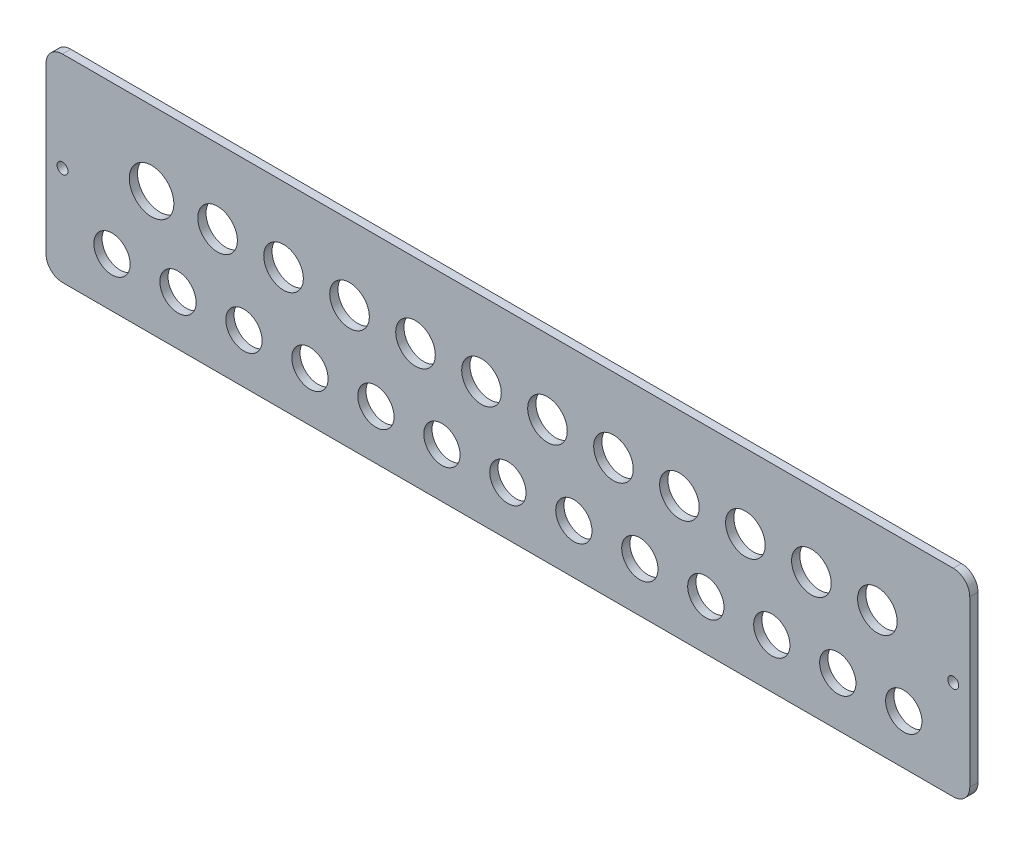
SolidWorks part; units mm, degrees
ref_plane "Front Plane" through (0, 0, 0) normal (0, 0, 1) x (1, 0, 0)
ref_plane "Top Plane" through (0, 0, 0) normal (0, 1, 0) x (1, 0, 0)
ref_plane "Right Plane" through (0, 0, 0) normal (1, 0, 0) x (0, 0, -1)
sketch "Sketch1" plane through (0, 0, 0) normal (0, 0, 1) x (1, 0, 0)
  line L1 (-270, -60) -> (270, -60)
  line L2 (-280, -50) -> (-280, 50)
  line L3 (-270, 60) -> (270, 60)
  line L4 (280, -50) -> (280, 50)
  line L5 (-280, -60) -> (280, 60) construction
  line L6 (-280, 60) -> (280, -60) construction
  arc A0 (280, 50) -> (270, 60) centre (270, 50) ccw
  arc A1 (270, -60) -> (280, -50) centre (270, -50) ccw
  arc A2 (-270, -60) -> (-280, -50) centre (-270, -50) cw
  arc A3 (-280, 50) -> (-270, 60) centre (-270, 50) cw
  point P0 (0, 0)
  dimension "D3" = 10
  dimension "D1" = 560
  dimension "D2" = 120
extrude "Boss-Extrude1" add sketch "Sketch1" along normal blind 5
hole_wizard "M6 Clearance Hole1" positions "Sketch3" profile "Sketch2" hole size "M6" standard "ANSI Metric"
sketch "Sketch3" plane through (0, 0, 5) normal (0, 0, 1) x (1, 0, 0)
  point P0 (270, 0)
  point P3 (-270, 0)
sketch "Sketch2" plane through (270, 0, 5) normal (1, 0, 0) x (0, -1, 0)
  line L0 (0, 0) -> (0, 7.9828)
  line L1 (0, 7.9828) -> (3.3, 6)
  line L2 (3.3, 6) -> (3.3, 0)
  line L5 (3.3, 0) -> (0, 0)
  line L10 (0, 7.9828) -> (-3.3, 6) construction
  line L11 (0, -6.35) -> (0, 107.95) construction
  dimension "Hole Dia." = 6.6
  dimension "Hole Depth" = 6
  dimension "Drill Angle" = 118
hole_wizard "M20 Clearance Hole1" positions "Sketch5" profile "Sketch4" hole size "M20" standard "ANSI Metric"
sketch "Sketch5" plane through (0, 0, 0) normal (0, 0, -1) x (-1, 0, 0)
  line L0 (-280, -50) -> (-280, 50) construction
  line L2 (270, -60) -> (-270, -60) construction
  point P0 (-240, -30)
  point P9 (-229.0327, -60)
  point P16 (-437.7698, 40.5082)
  dimension "D1" = 40
  dimension "D2" = 30
sketch "Sketch4" plane through (240, -30, 0) normal (1, 0, 0) x (0, 1, 0)
  line L0 (0, 0) -> (0, 12.6095)
  line L1 (0, 12.6095) -> (11, 6)
  line L2 (11, 6) -> (11, 0)
  line L5 (11, 0) -> (0, 0)
  line L10 (0, 12.6095) -> (-11, 6) construction
  line L11 (0, -6.35) -> (0, 107.95) construction
  dimension "Hole Dia." = 22
  dimension "Hole Depth" = 6
  dimension "Drill Angle" = 118
pattern_linear "LPattern1" count 13 spacing 40 along (-1, 0, 0) of "M20 Clearance Hole1"
hole_wizard "M22 Clearance Hole1" positions "Sketch7" profile "Sketch6" hole size "M22" standard "ANSI Metric"
sketch "Sketch7" plane through (0, 0, 0) normal (0, 0, -1) x (-1, 0, 0)
  line L0 (-280, -50) -> (-280, 50) construction
  circle A0 centre (-240, -30) radius 11 construction
  point P0 (-224, 15)
  dimension "D1" = 45
  dimension "D2" = 56
sketch "Sketch6" plane through (224, 15, 0) normal (1, 0, 0) x (0, 1, 0)
  line L0 (0, 0) -> (0, 13.2103)
  line L1 (0, 13.2103) -> (12, 6)
  line L2 (12, 6) -> (12, 0)
  line L5 (12, 0) -> (0, 0)
  line L10 (0, 13.2103) -> (-12, 6) construction
  line L11 (0, -6.35) -> (0, 107.95) construction
  dimension "Hole Dia." = 24
  dimension "Hole Depth" = 6
  dimension "Drill Angle" = 118
pattern_linear "LPattern2" count 12 spacing 40 along (-1, 0, 0) of "M22 Clearance Hole1"
hole_wizard "M25 Clearance Hole1" positions "Sketch9" profile "Sketch8" hole size "M25" standard "ANSI Metric"
sketch "Sketch9" plane through (0, 0, 0) normal (0, 0, -1) x (-1, 0, 0)
  point P0 (216, 15)
sketch "Sketch8" plane through (-216, 15, 0) normal (1, 0, 0) x (0, 1, 0)
  line L0 (0, 0) -> (0, 14.1116)
  line L1 (0, 14.1116) -> (13.5, 6)
  line L2 (13.5, 6) -> (13.5, 0)
  line L5 (13.5, 0) -> (0, 0)
  line L10 (0, 14.1116) -> (-13.5, 6) construction
  line L11 (0, -6.35) -> (0, 107.95) construction
  dimension "Hole Dia." = 27
  dimension "Hole Depth" = 6
  dimension "Drill Angle" = 118
